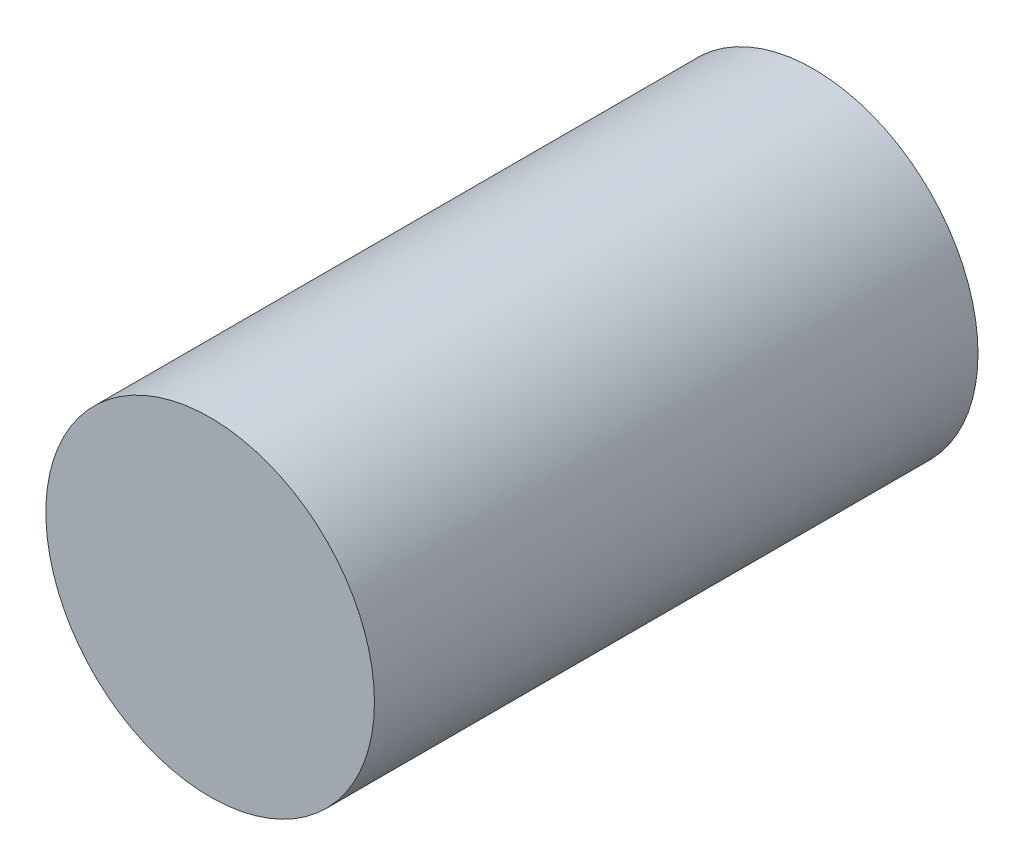
SolidWorks part; units mm, degrees
ref_plane "Front" through (0, 0, 0) normal (0, 0, 1) x (1, 0, 0)
ref_plane "Top" through (0, 0, 0) normal (0, 1, 0) x (1, 0, 0)
ref_plane "Right" through (0, 0, 0) normal (1, 0, 0) x (0, 0, -1)
sketch "Sketch1" plane through (0, 0, 0) normal (0, 0, 1) x (1, 0, 0)
  circle A0 centre (0, 0) radius 2.45
  dimension "D1" = 4.9
extrude "Boss-Extrude1" add sketch "Sketch1" along normal blind 9
